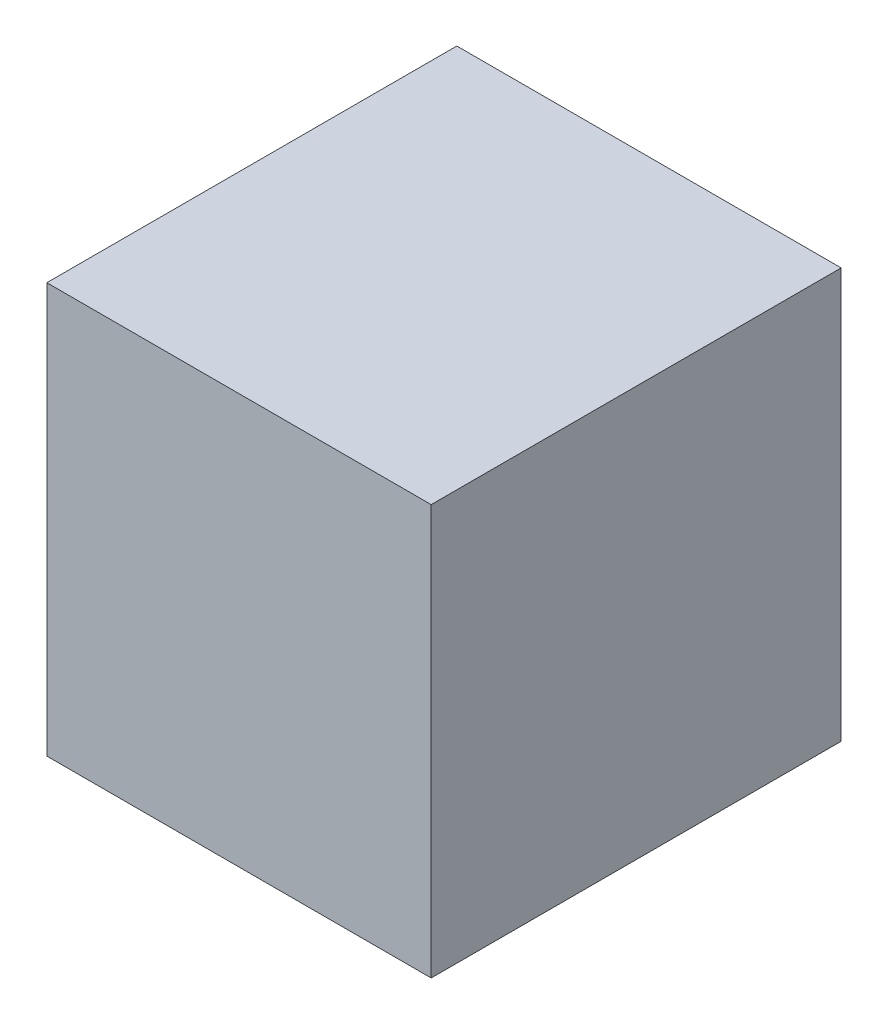
SolidWorks part; units mm, degrees
ref_plane "Front Plane" through (0, 0, 0) normal (0, 0, 1) x (1, 0, 0)
ref_plane "Top Plane" through (0, 0, 0) normal (0, 1, 0) x (1, 0, 0)
ref_plane "Right Plane" through (0, 0, 0) normal (1, 0, 0) x (0, 0, -1)
other "Configuration Table"
sketch "Sketch1" plane through (0, 0, 0) normal (0, 0, 1) x (1, 0, 0)
  line L1 (143, -8) -> (158, -8)
  line L2 (143, -8) -> (143, 8)
  line L3 (143, 8) -> (158, 8)
  line L4 (158, -8) -> (158, 8)
extrude "MTG_M12_soket_1" add sketch "Sketch1" against normal blind 16 from offset 8 separate body
